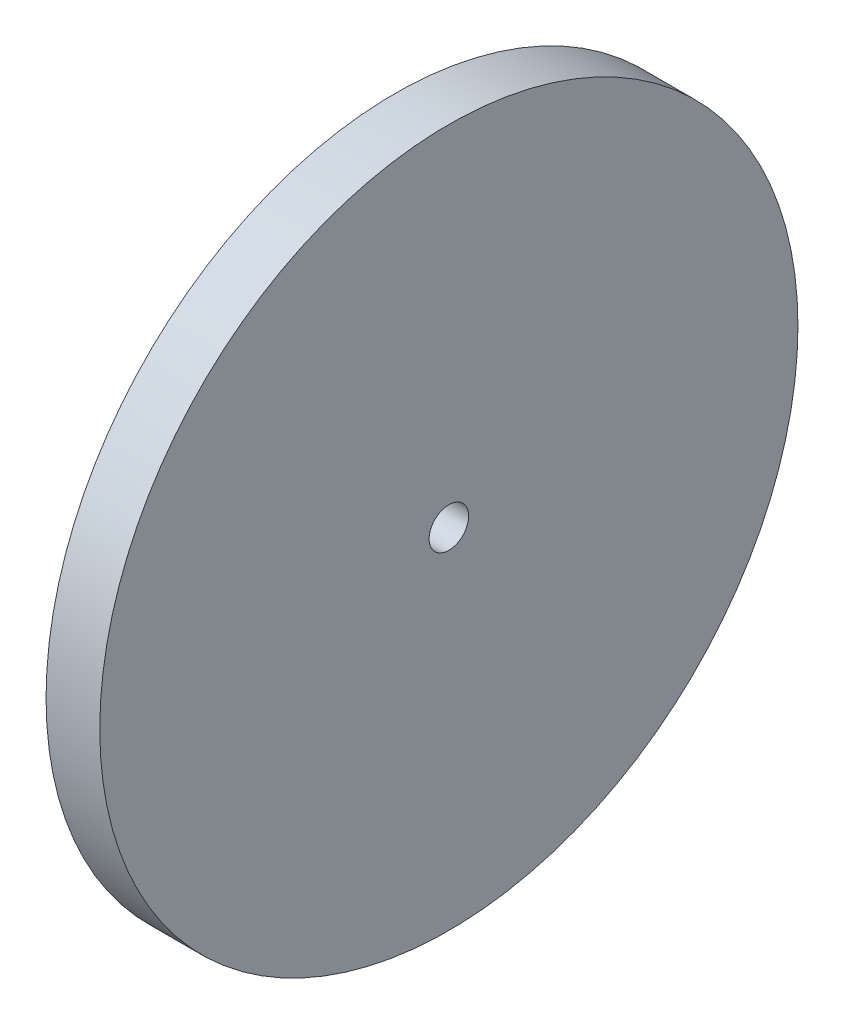
SolidWorks part; units mm, degrees
ref_plane "Front Plane" through (0, 0, 0) normal (0, 0, 1) x (1, 0, 0)
ref_plane "Top Plane" through (0, 0, 0) normal (0, 1, 0) x (1, 0, 0)
ref_plane "Right Plane" through (0, 0, 0) normal (1, 0, 0) x (0, 0, -1)
sketch "Sketch1" plane through (0, 0, 0) normal (1, 0, 0) x (0, 0, -1)
  circle A0 centre (0, 0) radius 65
  circle A1 centre (0, 0) radius 3.675
  dimension "D1" = 130
  dimension "D2" = 7.35
extrude "Boss-Extrude1" add sketch "Sketch1" along normal blind 10
